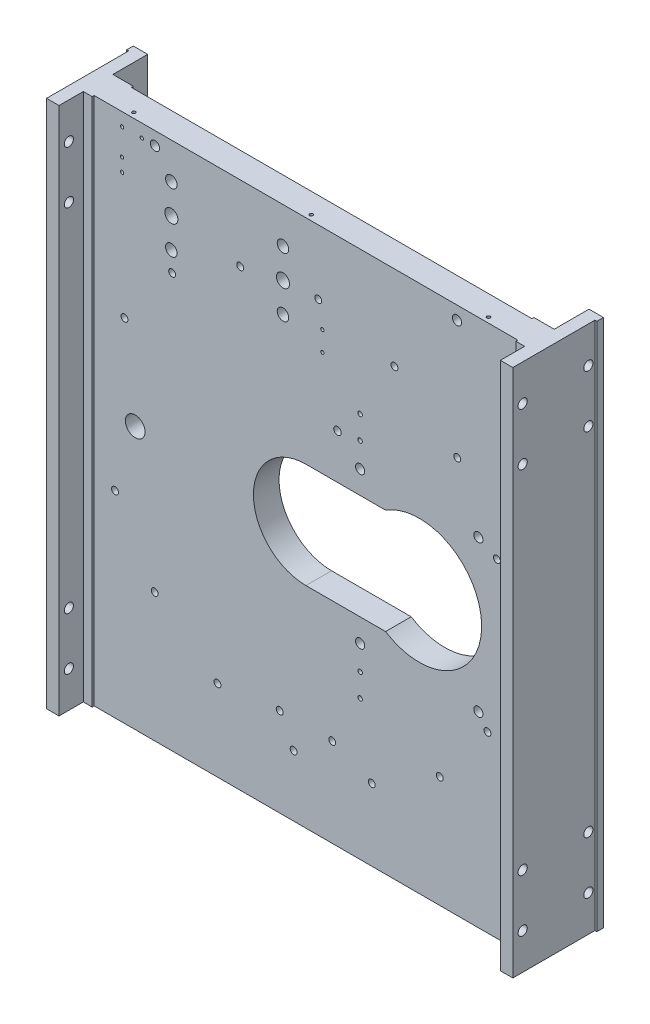
SolidWorks part; units mm, degrees
ref_plane "正面" through (0, 0, 0) normal (0, 0, 1) x (1, 0, 0)
ref_plane "平面" through (0, 0, 0) normal (0, 1, 0) x (1, 0, 0)
ref_plane "右側面" through (0, 0, 0) normal (1, 0, 0) x (0, 0, -1)
sketch "ｽｹｯﾁ1" plane through (0, 0, 0) normal (0, 1, 0) x (1, 0, 0)
  line L0 (-336, 37) -> (-322.5, 37)
  line L1 (-322.5, 37) -> (-322.5, 40)
  line L2 (-322.5, 40) -> (322.5, 40)
  line L3 (322.5, 40) -> (322.5, 37)
  line L4 (322.5, 37) -> (336, 37)
  line L5 (336, 37) -> (336, 82)
  line L6 (336, 82) -> (305, 82)
  line L7 (305, 82) -> (305, 79)
  line L8 (305, 79) -> (-305, 79)
  line L9 (-305, 79) -> (-305, 82)
  line L10 (-305, 82) -> (-336, 82)
  line L11 (-336, 82) -> (-336, 37)
extrude "ﾎﾞｽ - 押し出し1" add sketch "ｽｹｯﾁ1" along normal blind 805
sketch "ｽｹｯﾁ2" plane through (0, 0, 0) normal (0, 1, 0) x (1, 0, 0)
  line L0 (-355, 0) -> (-336, 0)
  line L1 (-336, 0) -> (-336, 135)
  line L2 (-336, 135) -> (-358, 135)
  line L3 (-358, 135) -> (-358, 125)
  line L4 (-358, 125) -> (-355, 125)
  line L5 (-355, 125) -> (-355, 0)
extrude "ﾎﾞｽ - 押し出し2" add sketch "ｽｹｯﾁ2" along normal blind 805
sketch "ｽｹｯﾁ3" plane through (0, 0, 0) normal (0, 1, 0) x (1, 0, 0)
  line L0 (355, 0) -> (336, 0)
  line L1 (336, 0) -> (336, 135)
  line L2 (336, 135) -> (358, 135)
  line L3 (358, 135) -> (358, 125)
  line L4 (358, 125) -> (355, 125)
  line L5 (355, 125) -> (355, 0)
extrude "ﾎﾞｽ - 押し出し3" add sketch "ｽｹｯﾁ3" along normal blind 805
sketch "ｽｹｯﾁ4" plane through (0, 0, 0) normal (0, 0, 1) x (1, 0, 0)
  line L0 (0, 320) -> (121.2652, 320)
  line L1 (121.2652, 320) -> (121.2652, 480)
  line L2 (121.2652, 480) -> (0, 480)
  line L3 (0, 480) -> (0, 320)
extrude "ｶｯﾄ - 押し出し1" cut sketch "ｽｹｯﾁ4" against normal through all and the other way through all
sketch "ｽｹｯﾁ5" plane through (0, 0, 0) normal (0, 0, 1) x (1, 0, 0)
  circle A0 centre (0, 400) radius 80
extrude "ｶｯﾄ - 押し出し2" cut sketch "ｽｹｯﾁ5" against normal through all and the other way through all
sketch "ｽｹｯﾁ6" plane through (0, 0, 0) normal (0, 0, 1) x (1, 0, 0)
  circle A0 centre (172.5, 400) radius 95
extrude "ｶｯﾄ - 押し出し3" cut sketch "ｽｹｯﾁ6" against normal through all and the other way through all
sketch "ｽｹｯﾁ7" plane through (0, 0, 0) normal (0, 0, 1) x (1, 0, 0)
  circle A0 centre (-260, 400) radius 15
extrude "ｶｯﾄ - 押し出し4" cut sketch "ｽｹｯﾁ7" against normal through all and the other way through all
sketch "ｽｹｯﾁ8" plane through (0, 0, 0) normal (0, 0, 1) x (1, 0, 0)
  circle A0 centre (290.747, 500.1122) radius 5.25
  circle A1 centre (230.3039, 603.7557) radius 5.25
  circle A2 centre (134.7991, 676.3792) radius 5.25
  circle A3 centre (18.7724, 706.9265) radius 5.25
  circle A4 centre (-100.1122, 690.747) radius 5.25
  circle A5 centre (-203.7557, 630.3039) radius 5.25
  circle A6 centre (-276.3792, 534.7991) radius 5.25
  circle A7 centre (-290.747, 299.8878) radius 5.25
  circle A8 centre (-230.3039, 196.2443) radius 5.25
  circle A9 centre (-134.7991, 123.6208) radius 5.25
  circle A10 centre (-18.7724, 93.0735) radius 5.25
  circle A11 centre (100.1122, 109.253) radius 5.25
  circle A12 centre (203.7557, 169.6961) radius 5.25
  circle A13 centre (276.3792, 265.2009) radius 5.25
extrude "ｶｯﾄ - 押し出し5" cut sketch "ｽｹｯﾁ8" against normal through all and the other way through all
sketch "ｽｹｯﾁ9" plane through (0, 0, 0) normal (0, 0, 1) x (1, 0, 0)
  circle A0 centre (-205, 660) radius 8.75
  circle A1 centre (-205, 750) radius 8.75
  circle A2 centre (-35, 660) radius 8.75
  circle A3 centre (-35, 750) radius 8.75
extrude "ｶｯﾄ - 押し出し6" cut sketch "ｽｹｯﾁ9" against normal through all and the other way through all
sketch "ｽｹｯﾁ10" plane through (0, 0, 0) normal (0, 0, 1) x (1, 0, 0)
  circle A0 centre (-205, 705) radius 10
  circle A1 centre (-35, 705) radius 10
extrude "ｶｯﾄ - 押し出し7" cut sketch "ｽｹｯﾁ10" against normal through all and the other way through all
sketch "ｽｹｯﾁ11" plane through (0, 0, 0) normal (0, 0, 1) x (1, 0, 0)
  circle A0 centre (82.5, 285) radius 7
  circle A1 centre (262.5, 285) radius 7
  circle A2 centre (82.5, 515) radius 7
  circle A3 centre (262.5, 515) radius 7
extrude "ｶｯﾄ - 押し出し8" cut sketch "ｽｹｯﾁ11" against normal through all and the other way through all
sketch "ｽｹｯﾁ12" plane through (0, 0, 0) normal (0, 0, 1) x (1, 0, 0)
  circle A0 centre (82.5, 212.5) radius 3.4
  circle A1 centre (82.5, 247.5) radius 3.4
  circle A2 centre (82.5, 552.5) radius 3.4
  circle A3 centre (82.5, 587.5) radius 3.4
extrude "ｶｯﾄ - 押し出し9" cut sketch "ｽｹｯﾁ12" against normal through all and the other way through all
sketch "ｽｹｯﾁ13" plane through (0, 0, 0) normal (0, 0, 1) x (1, 0, 0)
  circle A0 centre (-40, 135) radius 5.25
  circle A1 centre (40, 135) radius 5.25
extrude "ｶｯﾄ - 押し出し10" cut sketch "ｽｹｯﾁ13" against normal through all and the other way through all
sketch "ｽｹｯﾁ14" plane through (0, 0, 0) normal (0, 0, 1) x (1, 0, 0)
  circle A0 centre (25, 640) radius 2.5
  circle A1 centre (25, 670) radius 2.5
extrude "ｶｯﾄ - 押し出し11" cut sketch "ｽｹｯﾁ14" against normal through all and the other way through all
sketch "ｽｹｯﾁ15" plane through (0, 0, 0) normal (0, 0, 1) x (1, 0, 0)
  circle A0 centre (48, 548) radius 5.7225
extrude "ｶｯﾄ - 押し出し12" cut sketch "ｽｹｯﾁ15" against normal through all and the other way through all
sketch "ｽｹｯﾁ16" plane through (0, 0, 0) normal (0, 0, 1) x (1, 0, 0)
  circle A0 centre (-230, 785) radius 7
  circle A1 centre (230, 785) radius 7
extrude "ｶｯﾄ - 押し出し13" cut sketch "ｽｹｯﾁ16" against normal through all and the other way through all
sketch "ｽｹｯﾁ17" plane through (0, 0, 0) normal (1, 0, 0) x (0, 0, -1)
  circle A0 centre (15, 55) radius 7
  circle A1 centre (15, 135) radius 7
  circle A2 centre (15, 670) radius 7
  circle A3 centre (15, 750) radius 7
  circle A4 centre (115, 55) radius 7
  circle A5 centre (115, 135) radius 7
  circle A6 centre (115, 670) radius 7
  circle A7 centre (115, 750) radius 7
extrude "ｶｯﾄ - 押し出し14" cut sketch "ｽｹｯﾁ17" against normal through all and the other way through all
sketch "ｽｹｯﾁ18" plane through (0, 0, 0) normal (0, 1, 0) x (1, 0, 0)
  circle A0 centre (-270, 48) radius 2.5
  circle A1 centre (0, 48) radius 2.5
  circle A2 centre (270, 48) radius 2.5
sketch "ｽｹｯﾁ19" plane through (0, 0, 0) normal (0, 1, 0) x (1, 0, 0)
  circle A0 centre (-270, 48) radius 2.5
  circle A1 centre (0, 48) radius 2.5
  circle A2 centre (270, 48) radius 2.5
extrude "ｶｯﾄ - 押し出し16" cut sketch "ｽｹｯﾁ19" along normal blind 15
sketch "ｽｹｯﾁ20" plane through (0, 0, 0) normal (0, 0, 1) x (1, 0, 0)
  circle A0 centre (-280, 725) radius 2.5
  circle A1 centre (-280, 745) radius 2.5
  circle A2 centre (-280, 785) radius 2.5
  circle A3 centre (-250, 785) radius 2.5
extrude "ｶｯﾄ - 押し出し17" cut sketch "ｽｹｯﾁ20" against normal blind 55
ref_plane "平面1" through (0, 805, 0) normal (0, 1, 0) x (1, 0, 0)
sketch "ｽｹｯﾁ21" plane through (0, 805, 0) normal (0, 1, 0) x (1, 0, 0)
  circle A0 centre (-270, 48) radius 2.5
  circle A1 centre (0, 48) radius 2.5
  circle A2 centre (270, 48) radius 2.5
extrude "ｶｯﾄ - 押し出し18" cut sketch "ｽｹｯﾁ21" against normal blind 15
ref_plane "平面2" through (0, 0, -135) normal (0, 0, 1) x (1, 0, 0)
sketch "ｽｹｯﾁ22" plane through (0, 0, -135) normal (0, 0, 1) x (1, 0, 0)
  circle A0 centre (-348, 38) radius 2.5
  circle A1 centre (-348, 158) radius 2.5
sketch "ｽｹｯﾁ23" plane through (0, 0, -135) normal (0, 0, 1) x (1, 0, 0)
  circle A0 centre (-348, 38) radius 2.5
  circle A1 centre (-348, 158) radius 2.5
extrude "ｶｯﾄ - 押し出し20" cut sketch "ｽｹｯﾁ23" along normal blind 15
sketch "ｽｹｯﾁ24" plane through (0, 0, -135) normal (0, 0, 1) x (1, 0, 0)
  circle A0 centre (-260, 370) radius 2.5
  circle A1 centre (-260, 430) radius 2.5
sketch "ｽｹｯﾁ25" plane through (0, 0, -135) normal (0, 0, 1) x (1, 0, 0)
  circle A0 centre (-260, 370) radius 2.5
  circle A1 centre (-260, 430) radius 2.5
extrude "ｶｯﾄ - 押し出し22" cut sketch "ｽｹｯﾁ25" along normal blind 68
sketch "ｽｹｯﾁ26" plane through (0, 0, -135) normal (0, 0, 1) x (1, 0, 0)
  circle A0 centre (135, 640) radius 2.1
  circle A1 centre (250, 640) radius 2.1
sketch "ｽｹｯﾁ27" plane through (0, 0, -135) normal (0, 0, 1) x (1, 0, 0)
  circle A0 centre (135, 640) radius 2.1
  circle A1 centre (250, 640) radius 2.1
extrude "ｶｯﾄ - 押し出し24" cut sketch "ｽｹｯﾁ27" along normal blind 71
